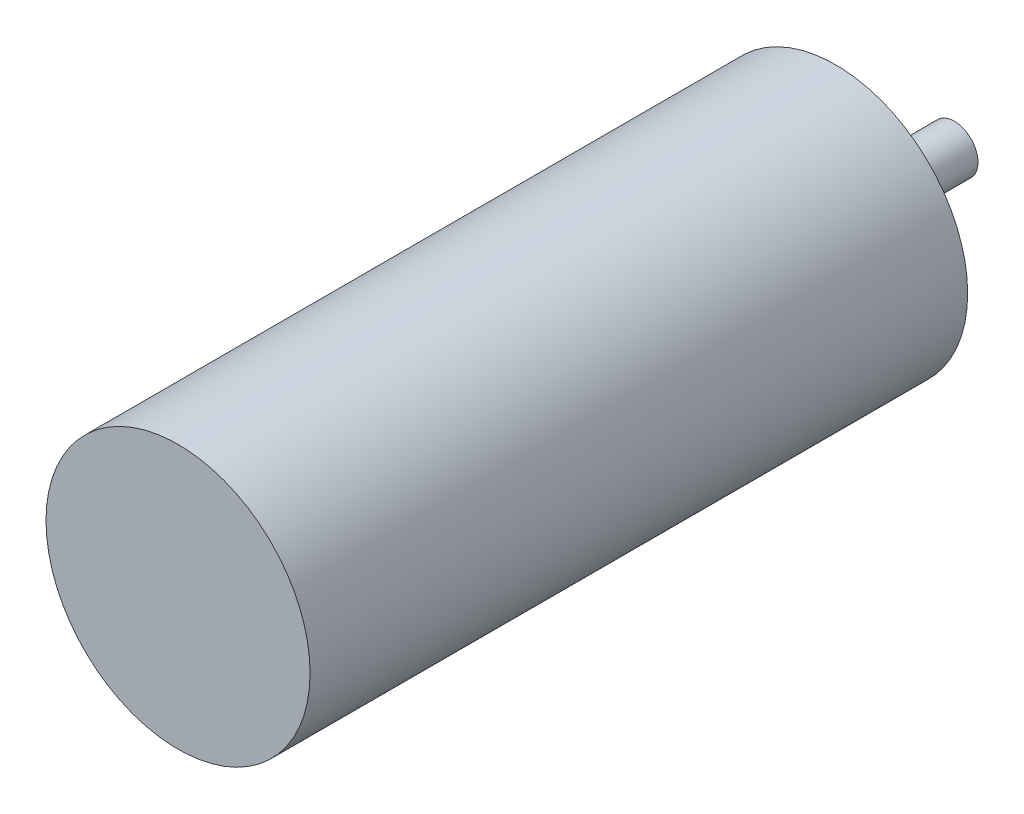
SolidWorks part; units mm, degrees
ref_plane "Front Plane" through (0, 0, 0) normal (0, 0, 1) x (1, 0, 0)
ref_plane "Top Plane" through (0, 0, 0) normal (0, 1, 0) x (1, 0, 0)
ref_plane "Right Plane" through (0, 0, 0) normal (1, 0, 0) x (0, 0, -1)
sketch "Sketch3" plane through (0, 0, 0) normal (0, 0, 1) x (1, 0, 0)
  circle A0 centre (0, 0) radius 22.25
extrude "Boss-Extrude1" add sketch "Sketch3" along normal blind 110.7999 contours A0
sketch "Sketch4" plane through (0, 0, 0) normal (0, 0, -1) x (-1, 0, 0)
  circle A0 centre (0, 0) radius 4
extrude "Boss-Extrude2" add sketch "Sketch4" along normal blind 20
